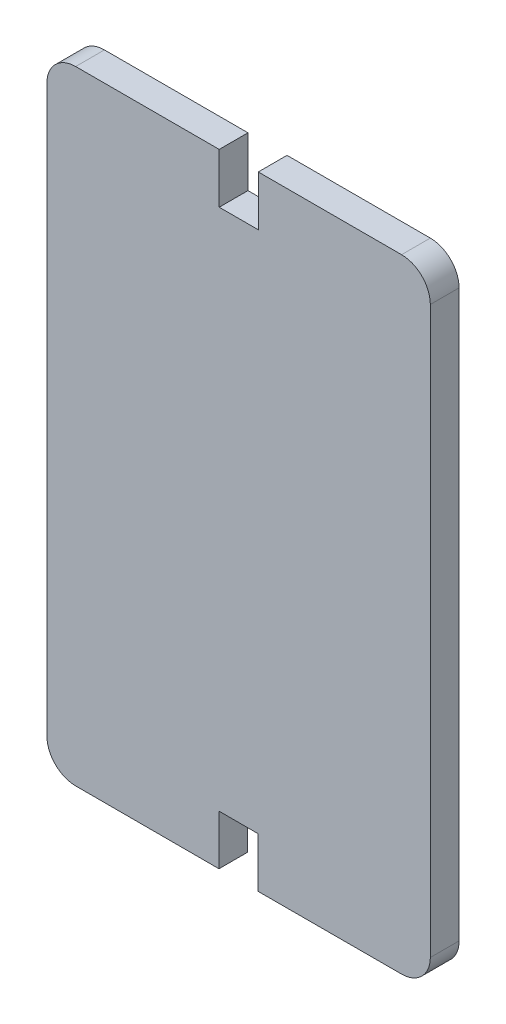
SolidWorks part; units mm, degrees
ref_plane "Front Plane" through (0, 0, 0) normal (0, 0, 1) x (1, 0, 0)
ref_plane "Top Plane" through (0, 0, 0) normal (0, 1, 0) x (1, 0, 0)
ref_plane "Right Plane" through (0, 0, 0) normal (1, 0, 0) x (0, 0, -1)
sketch "Sketch1" plane through (0, 0, 0) normal (0, 0, 1) x (1, 0, 0)
  line L12 (3, 0) -> (17.95, -0.01)
  line L13 (17.95, -0.01) -> (17.95, 5.2)
  line L14 (17.95, 5.2) -> (22.025, 5.2)
  line L15 (22.025, 5.2) -> (22.025, -0.01)
  line L16 (22.025, -0.01) -> (37, 0)
  line L17 (40, 3) -> (40, 62)
  line L18 (37, 65) -> (22.05, 65)
  line L19 (22.05, 65) -> (22.05, 59.775)
  line L20 (22.05, 59.775) -> (17.975, 59.775)
  line L21 (17.975, 59.775) -> (17.975, 65)
  line L22 (17.975, 65) -> (3, 65)
  line L23 (0, 62) -> (0, 3)
  line L24 (3, 0) -> (17.95, -0.01)
  line L25 (17.95, -0.01) -> (17.95, 5.2)
  line L26 (17.95, 5.2) -> (22.025, 5.2)
  line L27 (22.025, 5.2) -> (22.025, -0.01)
  line L28 (22.025, -0.01) -> (37, 0)
  line L29 (40, 3) -> (40, 62)
  line L30 (37, 65) -> (22.05, 65)
  line L31 (22.05, 65) -> (22.05, 59.775)
  line L32 (22.05, 59.775) -> (17.975, 59.775)
  line L33 (17.975, 59.775) -> (17.975, 65)
  line L34 (17.975, 65) -> (3, 65)
  line L35 (0, 62) -> (0, 3)
  arc A4 (0, 3) -> (3, 0) centre (3, 3) ccw
  arc A5 (37, 0) -> (40, 3) centre (37, 3) ccw
  arc A6 (40, 62) -> (37, 65) centre (37, 62) ccw
  arc A7 (3, 65) -> (0, 62) centre (3, 62) ccw
  arc A8 (0, 3) -> (3, 0) centre (3, 3) ccw
  arc A9 (37, 0) -> (40, 3) centre (37, 3) ccw
  arc A10 (40, 62) -> (37, 65) centre (37, 62) ccw
  arc A11 (3, 65) -> (0, 62) centre (3, 62) ccw
  dimension "D1" = 0
extrude "Boss-Extrude1" add sketch "Sketch1" along normal blind 3 contours A8 L24 L25 L26 L27 L28 A9 L29 A10 L30 L31 L32 L33 L34 A11 L35
